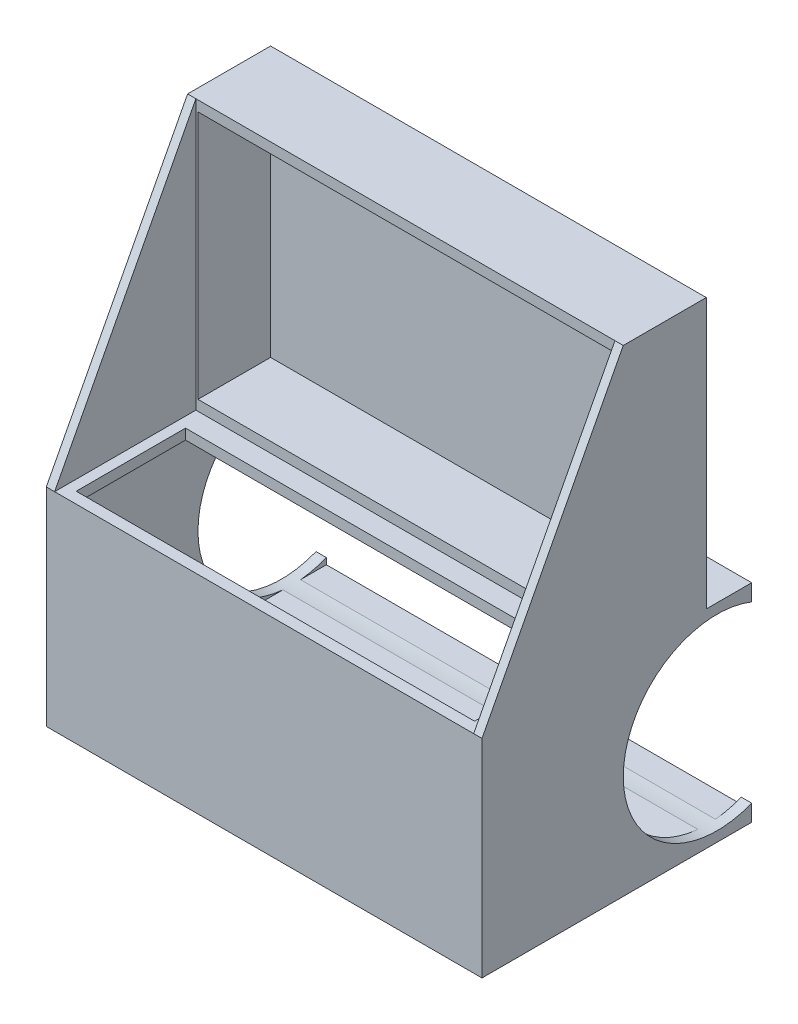
SolidWorks part; units mm, degrees
ref_plane "前视基准面" through (0, 0, 0) normal (0, 0, 1) x (1, 0, 0)
ref_plane "上视基准面" through (0, 0, 0) normal (0, 1, 0) x (1, 0, 0)
ref_plane "右视基准面" through (0, 0, 0) normal (1, 0, 0) x (0, 0, -1)
other "Configuration Table"
sketch "草图2" plane through (0, 0, 0) normal (0, 0, 1) x (1, 0, 0)
  line L1 (-105, 50) -> (105, 50)
  line L2 (-105, 50) -> (-105, -50)
  line L3 (-105, -50) -> (105, -50)
  line L4 (105, 50) -> (105, -50)
  line L5 (-105, 50) -> (105, -50) construction
  line L6 (-105, -50) -> (105, 50) construction
  point P0 (0, 0)
  dimension "D1" = 210
  dimension "D2" = 100
extrude "凸台-拉伸1" add sketch "草图2" along normal blind 130
sketch "草图3" plane through (0, 0, 0) normal (0, 0, 1) x (1, 0, 0)
  line L1 (-100, 45) -> (100, 45)
  line L2 (-100, 45) -> (-100, -45)
  line L3 (-100, -45) -> (100, -45)
  line L4 (100, 45) -> (100, -45)
  line L5 (-100, 45) -> (100, -45) construction
  line L6 (-100, -45) -> (100, 45) construction
  point P0 (0, 0)
  dimension "D1" = 200
  dimension "D2" = 90
extrude "切除-拉伸1" cut sketch "草图3" along normal blind 125 contours L2 L1 L4 L3
sketch "草图4" plane through (0, 0, 0) normal (0, 1, 0) x (1, 0, 0)
  line L1 (-35, -40) -> (35, -40)
  line L2 (-35, -40) -> (-35, -125)
  line L3 (-35, -125) -> (35, -125)
  line L4 (35, -40) -> (35, -125)
  line L5 (-35, -40) -> (35, -125) construction
  line L6 (-35, -125) -> (35, -40) construction
  line L9 (105, -130) -> (105, 0) construction
  line L10 (105, -130) -> (-105, -130) construction
  point P0 (0, -82.5)
  dimension "D1" = 70
  dimension "D2" = 85
  dimension "D3" = 5
  dimension "D4" = 105
extrude "切除-拉伸2" cut sketch "草图4" against normal blind 125
sketch "草图5" plane through (0, 0, 0) normal (1, 0, 0) x (0, 0, -1)
  line L0 (-130, 0) -> (-62, 0)
  line L1 (-130, -50) -> (-130, 50) construction
  line L2 (-130, -50) -> (0, -50) construction
  line L4 (0, -50) -> (0, 50) construction
  line L8 (0, 42) -> (0, -42)
  arc A0 (0, 42) -> (0, -42) centre (-16.7013, 0) ccw
  dimension "D1" = 68
  dimension "D2" = 50
extrude "切除-拉伸4" cut sketch "草图5" against normal mid plane 300 contours A0 L8
sketch "草图6" plane through (105, 0, 0) normal (1, 0, 0) x (0, 0, -1)
  line L0 (-61.9001, 50) -> (-61.9001, 174.6157)
  line L1 (-130, 50) -> (0, 50) construction
  line L2 (-61.9001, 50) -> (-21.9001, 50)
  line L3 (-21.9001, 50) -> (-21.9001, 180)
  line L4 (-21.9001, 180) -> (-61.9001, 180)
  line L5 (-61.9001, 180) -> (-61.9001, 174.6157)
  dimension "D1" = 40
  dimension "D2" = 21.9001
  dimension "D3" = 130
extrude "凸台-拉伸3" add sketch "草图6" against normal blind 210
sketch "草图7" plane through (0, 0, 61.9001) normal (0, 0, 1) x (1, 0, 0)
  line L0 (105, 180) -> (105, 50) construction
  line L9 (-100, 175) -> (100, 175)
  line L10 (-100, 175) -> (-100, 55)
  line L11 (-100, 55) -> (100, 55)
  line L12 (100, 175) -> (100, 55)
  line L13 (-100, 175) -> (100, 55) construction
  line L14 (-100, 55) -> (100, 175) construction
  line L15 (-105, 50) -> (105, 50) construction
  point P0 (0, 115)
  dimension "D1" = 200
  dimension "D2" = 120
  dimension "D3" = 5
  dimension "D4" = 5
extrude "切除-拉伸7" cut sketch "草图7" against normal blind 35
sketch "草图11" plane through (105, 0, 0) normal (1, 0, 0) x (0, 0, -1)
  line L0 (-130, 50) -> (-61.9001, 180)
  line L1 (-61.9001, 180) -> (-130, 50)
  line M7 (-61.9001, 180) -> (-61.9001, 50)
  line M8 (-61.9001, 50) -> (-130, 50)
extrude "凸台-拉伸6" add sketch "草图11" against normal blind 4 contours L0 M8 M7
sketch "草图12" plane through (-105, 0, 0) normal (-1, 0, 0) x (0, 0, 1)
  line L0 (61.9001, 180) -> (130, 50)
  line L1 (130, 50) -> (61.9001, 180)
  line M6 (130, 50) -> (61.9001, 50)
  line M7 (61.9001, 50) -> (61.9001, 180)
extrude "凸台-拉伸7" add sketch "草图12" against normal blind 4 contours L0 M7 M6
sketch "草图13" plane through (0, 50, 0) normal (0, 1, 0) x (1, 0, 0)
  line L0 (101, -61.9001) -> (101, -130) construction
  line L5 (-96, -71.9001) -> (96, -71.9001)
  line L6 (-96, -71.9001) -> (-96, -124.5898)
  line L7 (-96, -124.5898) -> (96, -124.5898)
  line L8 (96, -71.9001) -> (96, -124.5898)
  line L9 (-96, -71.9001) -> (96, -124.5898) construction
  line L10 (-96, -124.5898) -> (96, -71.9001) construction
  line L11 (-101, -130) -> (-101, -61.9001) construction
  line L12 (-101, -61.9001) -> (101, -61.9001) construction
  point P0 (0, -98.2449)
  point P12 (0, -61.9001)
  dimension "D1" = 5
  dimension "D2" = 5
  dimension "D3" = 10
extrude "切除-拉伸9" cut sketch "草图13" against normal blind 5
